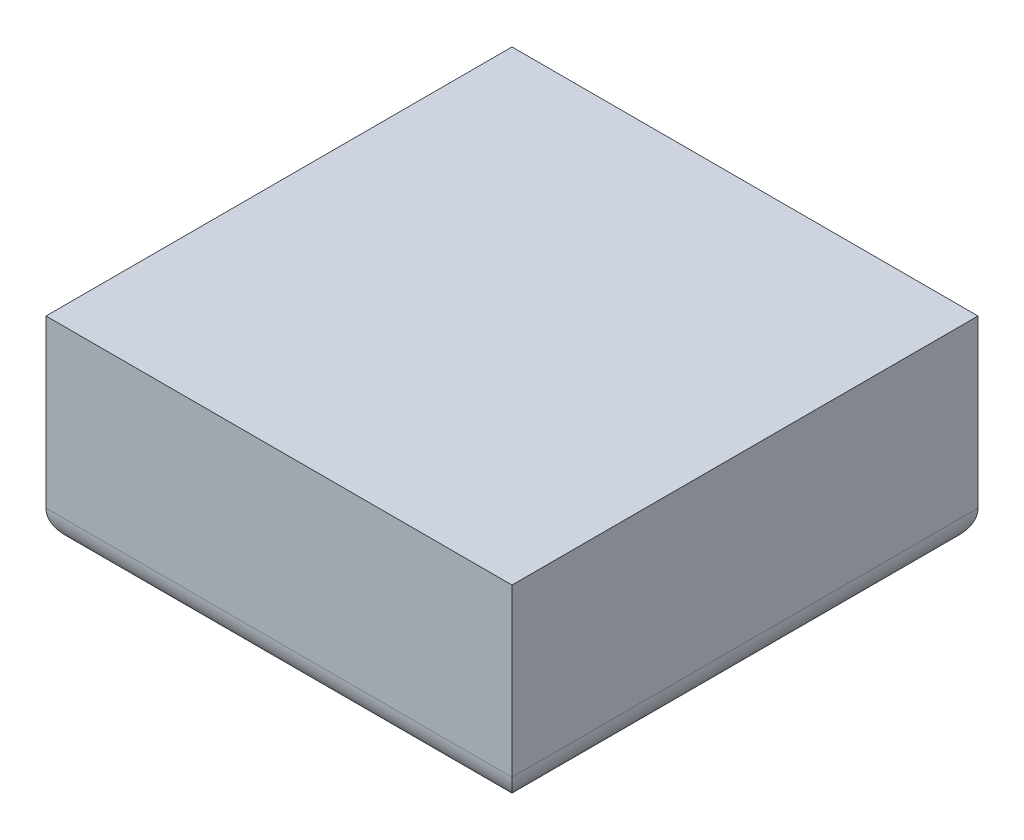
SolidWorks part; units mm, degrees
ref_plane "Front Plane" through (0, 0, 0) normal (0, 0, 1) x (1, 0, 0)
ref_plane "Top Plane" through (0, 0, 0) normal (0, 1, 0) x (1, 0, 0)
ref_plane "Right Plane" through (0, 0, 0) normal (1, 0, 0) x (0, 0, -1)
sketch "Sketch1" plane through (0, 0, 0) normal (0, 1, 0) x (1, 0, 0)
  line L1 (0, 0) -> (70, 0)
  line L2 (0, 0) -> (0, 70)
  line L3 (0, 70) -> (70, 70)
  line L4 (70, 0) -> (70, 70)
  dimension "D1" = 70
  dimension "D2" = 70
extrude "Boss-Extrude1" add sketch "Sketch1" along normal blind 30
fillet "Fillet1" radius 5 4 edges at (35, 0, 0) (70, 0, -35) (35, 0, -70) (0, 0, -35)
